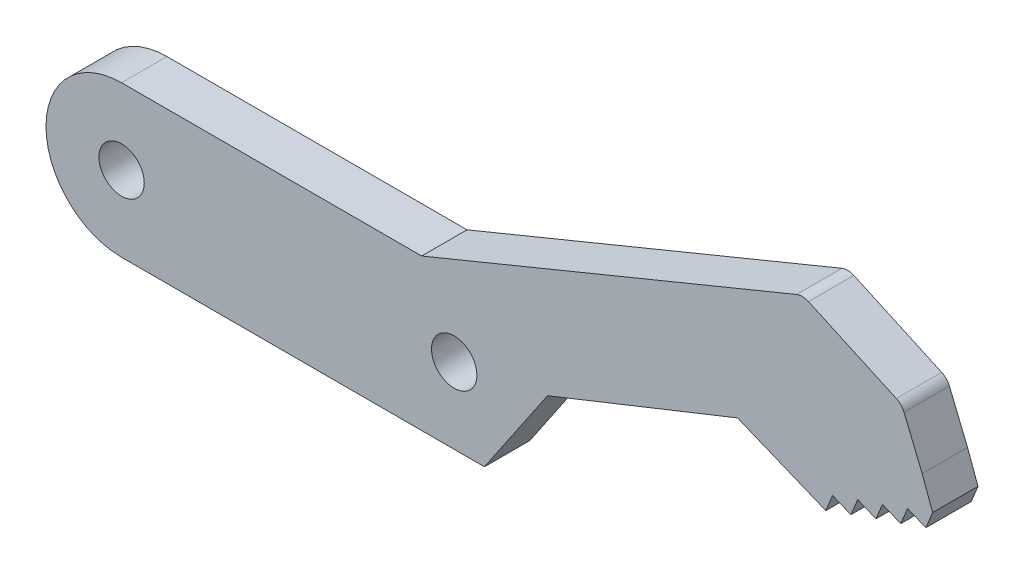
SolidWorks part; units mm, degrees
ref_plane "Front Plane" through (0, 0, 0) normal (0, 0, 1) x (1, 0, 0)
ref_plane "Top Plane" through (0, 0, 0) normal (0, 1, 0) x (1, 0, 0)
ref_plane "Right Plane" through (0, 0, 0) normal (1, 0, 0) x (0, 0, -1)
sketch "Sketch1" plane through (0, 0, 0) normal (0, 0, 1) x (1, 0, 0)
  line L0 (0, 0) -> (22, 0) construction
  line L1 (0, 5) -> (19.85, 5)
  line L2 (0, -5) -> (22, -5)
  line L3 (19.85, 5) -> (44.6431, 15.1937)
  line L4 (45.4379, 15.1788) -> (51.2451, 12.5335)
  line L5 (51.7554, 12.0038) -> (52.955, 9.0863)
  line L6 (24, -5) -> (22, -5)
  line L7 (24, -5) -> (28.1744, 1.1586)
  line L8 (28.1744, 1.1586) -> (40.742, 6.17)
  line L9 (40.742, 6.17) -> (46.5818, 3.7797)
  line L10 (46.5818, 3.7797) -> (47.0288, 4.8718)
  line L11 (47.0288, 4.8718) -> (48.2418, 4.3753)
  line L12 (48.2418, 4.3753) -> (48.6888, 5.4674)
  line L13 (48.6888, 5.4674) -> (49.9018, 4.9709)
  line L14 (49.9018, 4.9709) -> (50.3274, 6.0107)
  line L15 (50.3274, 6.0107) -> (51.5404, 5.5142)
  line L16 (51.5404, 5.5142) -> (51.9874, 6.6063)
  line L17 (51.9874, 6.6063) -> (53.2004, 6.1098)
  line L18 (53.2004, 6.1098) -> (53.6474, 7.2018)
  line L19 (53.6474, 7.2018) -> (52.955, 9.0863)
  arc A0 (0, 5) -> (0, -5) centre (0, 0) ccw
  circle A2 centre (0, 0) radius 1.5
  circle A3 centre (22, 0) radius 1.5
  arc A4 (51.2451, 12.5335) -> (51.7554, 12.0038) centre (50.8306, 11.6235) cw
  arc A5 (44.6431, 15.1937) -> (45.4379, 15.1788) centre (45.0233, 14.2688) cw
  point P3 (11, 0)
  point P18 (51.605, 12.3696)
  point P21 (45.0437, 15.3584)
  point P22 (24, -5)
  dimension "D3" = 3
  dimension "D4" = 3
  dimension "D12" = 1
  dimension "D2" = 5
  dimension "D5" = 19.85
  dimension "D6" = 157.65
  dimension "D7" = 27.24
  dimension "D8" = 133.16
  dimension "D9" = 7.21
  dimension "D10" = 136.84
  dimension "D11" = 3.55
  dimension "D13" = 24
  dimension "D14" = 55.87
  dimension "D15" = 7.44
  dimension "D16" = 214.13
  dimension "D17" = 13.53
  dimension "D18" = 224
  dimension "D19" = 6.31
  dimension "D20" = 1.18
  dimension "D21" = 1.66
  dimension "D22" = 2.0076
  dimension "D23" = 10
  dimension "D24" = 22
extrude "Boss-Extrude1" add sketch "Sketch1" along normal blind 3
